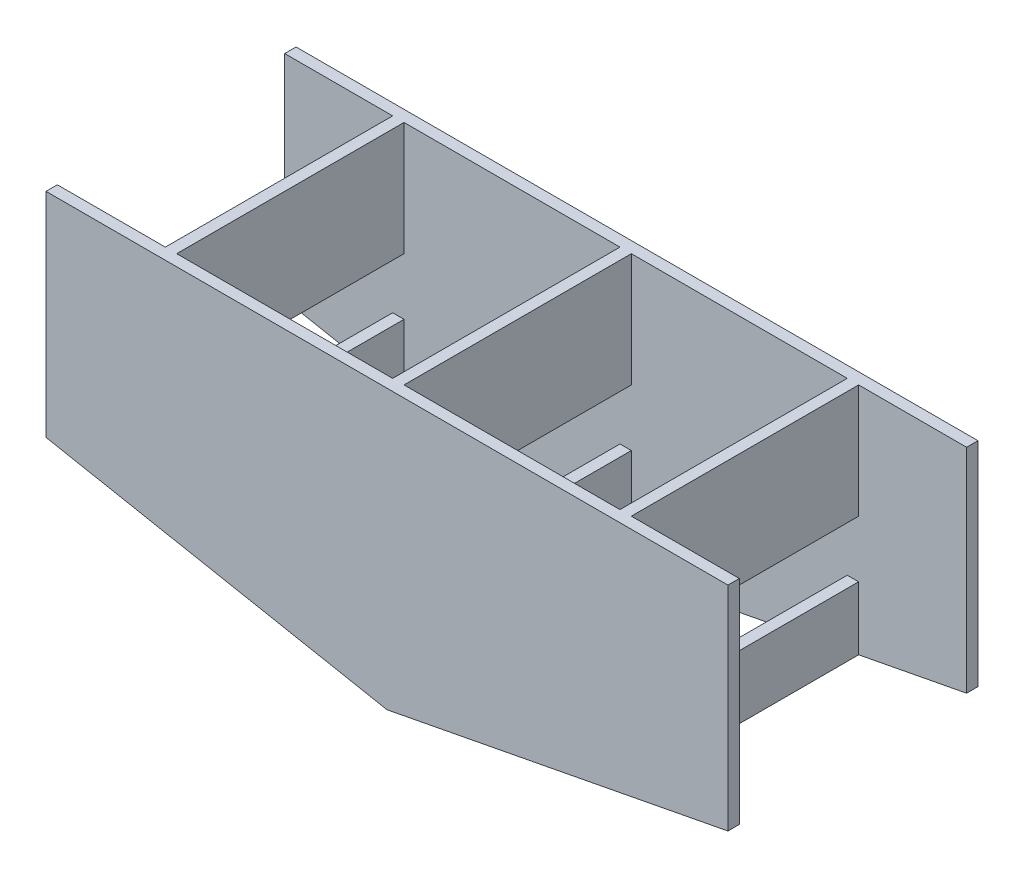
SolidWorks part; units mm, degrees
ref_plane "Front" through (0, 0, 0) normal (0, 0, 1) x (1, 0, 0)
ref_plane "Top" through (0, 0, 0) normal (0, 1, 0) x (1, 0, 0)
ref_plane "Right" through (0, 0, 0) normal (1, 0, 0) x (0, 0, -1)
sketch "Sketch1" plane through (0, 0, 0) normal (0, 0, 1) x (1, 0, 0)
  line L0 (-152.4, 62.23) -> (0, 62.23) construction
  line L1 (-152.4, -62.23) -> (152.4, -62.23) construction
  line L2 (-152.4, -62.23) -> (-152.4, 62.23) construction
  line L3 (-152.4, 62.23) -> (152.4, 62.23) construction
  line L4 (152.4, -62.23) -> (152.4, 62.23) construction
  line L5 (-152.4, -62.23) -> (152.4, 62.23) construction
  line L6 (-152.4, 62.23) -> (152.4, -62.23) construction
  line L7 (-152.4, 62.23) -> (-152.4, -33.02)
  line L8 (-152.4, -33.02) -> (0, -62.23)
  line L9 (0, -62.23) -> (152.4, -32.9764)
  line L10 (152.4, -32.9764) -> (152.4, 62.23)
  line L11 (152.4, 62.23) -> (-152.4, 62.23)
  point P0 (0, 0)
  dimension "D1" = 304.8
  dimension "D2" = 124.46
  dimension "D3" = 95.25
extrude "Boss-Extrude1" add sketch "Sketch1" against normal blind 111.76
ref_plane "Plane1" through (0, 0, -5.08) normal (0, 0, 1) x (1, 0, 0)
sketch "Sketch2" plane through (0, 0, 0) normal (0, 0, 1) x (1, 0, 0)
  line L0 (-152.4, -33.02) -> (-152.4, -13.97) construction
  line L1 (-152.4, 62.23) -> (-152.4, -33.02) construction
  line L2 (152.4, -32.9764) -> (152.4, 62.23) construction
  line L3 (-152.4, -13.97) -> (152.4, -13.97)
  line L4 (-152.4, -13.97) -> (-152.4, 11.43)
  line L5 (-152.4, 11.43) -> (152.4, 11.43)
  line L6 (152.4, -13.97) -> (152.4, 11.43)
  dimension "D1" = 19.05
  dimension "D2" = 25.4
sketch "Sketch5" plane through (0, 0, -5.08) normal (0, 0, 1) x (1, 0, 0)
  line L1 (-152.4, 11.43) -> (152.4, 11.43)
  line L2 (-152.4, 11.43) -> (-152.4, -13.97)
  line L3 (-152.4, -13.97) -> (152.4, -13.97)
  line L4 (152.4, 11.43) -> (152.4, -13.97)
  dimension "D1" = 19.05
  dimension "D2" = 25.4
extrude "Cut-Extrude3" cut sketch "Sketch5" against normal blind 101.6
sketch "Sketch3" plane through (0, 62.23, 0) normal (0, 1, 0) x (1, 0, 0)
  line L0 (152.4, 111.76) -> (-152.4, 111.76) construction
  line L1 (-2.54, 5.08) -> (-99.06, 5.08)
  line L2 (-2.54, 5.08) -> (-2.54, 106.68)
  line L3 (-2.54, 106.68) -> (-99.06, 106.68)
  line L4 (-99.06, 5.08) -> (-99.06, 106.68)
  line L5 (152.4, 0) -> (-152.4, 0) construction
  line L6 (0, 0) -> (0, 111.76) construction
  line L7 (2.54, 106.68) -> (99.06, 106.68)
  line L8 (99.06, 5.08) -> (99.06, 106.68)
  line L9 (2.54, 5.08) -> (99.06, 5.08)
  line L10 (2.54, 5.08) -> (2.54, 106.68)
  line L11 (-152.4, 111.76) -> (-152.4, 0) construction
  line L12 (-104.14, 106.68) -> (-152.4, 106.68)
  line L13 (-104.14, 106.68) -> (-104.14, 5.08)
  line L14 (-104.14, 5.08) -> (-152.4, 5.08)
  line L15 (-152.4, 106.68) -> (-152.4, 5.08)
  line L16 (104.14, 5.08) -> (152.4, 5.08)
  line L17 (152.4, 106.68) -> (152.4, 5.08)
  line L18 (104.14, 106.68) -> (152.4, 106.68)
  line L19 (104.14, 106.68) -> (104.14, 5.08)
  dimension "D1" = 2.54
  dimension "D2" = 96.52
  dimension "D3" = 5.08
  dimension "D4" = 5.08
  dimension "D5" = 5.08
  dimension "D6" = 5.08
  dimension "D7" = 5.08
extrude "Cut-Extrude4" cut sketch "Sketch3" against normal through all both and the other way through all
